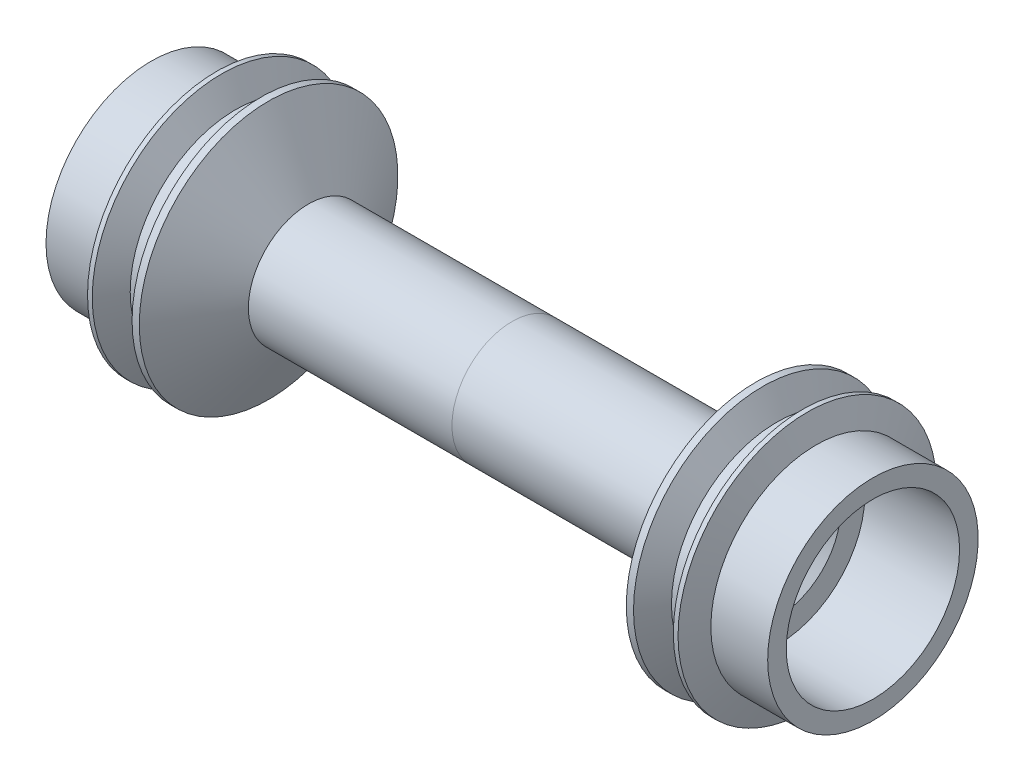
SolidWorks part; units mm, degrees
ref_plane "Front Plane" through (0, 0, 0) normal (0, 0, 1) x (1, 0, 0)
ref_plane "Top Plane" through (0, 0, 0) normal (0, 1, 0) x (1, 0, 0)
ref_plane "Right Plane" through (0, 0, 0) normal (1, 0, 0) x (0, 0, -1)
sketch "Sketch2" plane through (0, 0, 0) normal (0, 0, 1) x (1, 0, 0)
  line L0 (0, 0) -> (0, 28.4375) construction
  line L1 (-19.05, 4.575) -> (-14.05, 4.575) construction
  line L2 (-19.05, 4.575) -> (-19.05, -4.575) construction
  line L3 (-19.05, -4.575) -> (-14.05, -4.575) construction
  line L4 (-14.05, 4.575) -> (-14.05, -4.575) construction
  line L5 (-19.05, 4.575) -> (-14.05, -4.575) construction
  line L6 (-19.05, -4.575) -> (-14.05, 4.575) construction
  line L7 (14.05, 4.5) -> (49.5332, 4.5) construction
  line L8 (14.05, 4.5) -> (14.05, -4.5) construction
  line L9 (14.05, -4.5) -> (49.5332, -4.5) construction
  line L10 (49.5332, 4.5) -> (49.5332, -4.5) construction
  line L11 (14.05, 4.5) -> (49.5332, -4.5) construction
  line L12 (14.05, -4.5) -> (49.5332, 4.5) construction
  line L13 (-19.05, 0) -> (49.5332, 0) construction
  line L14 (-19.05, 5.5562) -> (-16.05, 5.5562)
  line L15 (-16.05, 5.5562) -> (-15.5878, 6.8262)
  line L16 (-15.5878, 6.8262) -> (-15.3382, 6.8262)
  line L19 (-13.2368, 6.8262) -> (-12.8558, 6.8262)
  line L20 (-12.8558, 6.8262) -> (-10.7477, 3.175)
  line L21 (-10.7477, 3.175) -> (0, 3.175)
  line L22 (-19.05, 5.5562) -> (-19.05, 4.575)
  line L23 (-19.05, 4.575) -> (-14.05, 4.575)
  line L24 (-14.05, 4.575) -> (-14.05, 0)
  line L25 (-14.05, 0) -> (0, 0)
  line L26 (0, 0) -> (0, 3.175)
  line L27 (-33.5594, -5.5562) -> (-33.5594, 5.5562) construction
  line L28 (-14.2875, 5.5562) -> (-14.2875, 7.68) construction
  line L29 (-14.2875, 5.5562) -> (14.2875, 5.5562) construction
  line L30 (-19.05, 5.5562) -> (19.05, 5.5562) construction
  line L31 (0, 1.6) -> (-6.5, 1.6)
  line L32 (-6.5, 1.6) -> (-8.1, 0)
  line L33 (-6.5, 1.6) -> (-6.5, -1.6) construction
  line L34 (-6.5, 1.6) -> (6.5, 1.6) construction
  line L35 (-14.05, 1.7145) -> (-9.225, 1.7145)
  line L36 (-9.225, 1.7145) -> (-9.225, 0)
  line L37 (-14.05, 3.305) -> (-13.542, 2.797)
  line L38 (-9.225, 1.7145) -> (-22.225, 1.7145) construction
  line L39 (-9.225, 1.7145) -> (-9.225, -1.7145) construction
  line L40 (-9.225, -1.7145) -> (-22.225, -1.7145) construction
  line L41 (-22.225, 1.7145) -> (-22.225, -1.7145) construction
  line L42 (-13.542, 2.797) -> (-13.542, 0)
  line L43 (-15.3382, 6.8262) -> (-14.605, 5.5562)
  line L44 (-14.605, 5.5562) -> (-13.97, 5.5562)
  line L45 (-13.97, 5.5562) -> (-13.2368, 6.8262)
  point P0 (-16.55, 0)
  point P5 (31.7916, 0)
  point P27 (-33.5594, 0)
  point P28 (-13.0463, 6.8262)
  point P29 (-6.5, 0)
  point P31 (0, 0)
  point P33 (0, 5.5562)
  point P36 (0, 1.6)
  point P48 (-9.225, 0)
  point P51 (0, 5.5562)
  point P54 (-14.2875, 5.5562)
  dimension "D1" = 5
  dimension "D3" = 3.175
  dimension "D4" = 11.1125
  dimension "D5" = 9.15
  dimension "D6" = 60
  dimension "D7" = 60
  dimension "D8" = 1.27
  dimension "D9" = 70
  dimension "D10" = 28.575
  dimension "D11" = 38.1
  dimension "D12" = 0.381
  dimension "D13" = 45
  dimension "D14" = 13
  dimension "D15" = 3.2
  dimension "D16" = 3.429
  dimension "D17" = 3.175
  dimension "D18" = 1.27
  dimension "D19" = 0.508
  dimension "D20" = 45
  dimension "D21" = 13
  dimension "D22" = 3
  dimension "D23" = 0.635
revolve "Revolve1" add sketch "Sketch2" angle 360 about L13
mirror "Mirror1" about plane through (0, 0, 0) normal (1, 0, 0) of bodies 101
chamfer "Chamfer1" distance 0.508 angle 45 1 edges at (-19.05, 0, 4.575)
